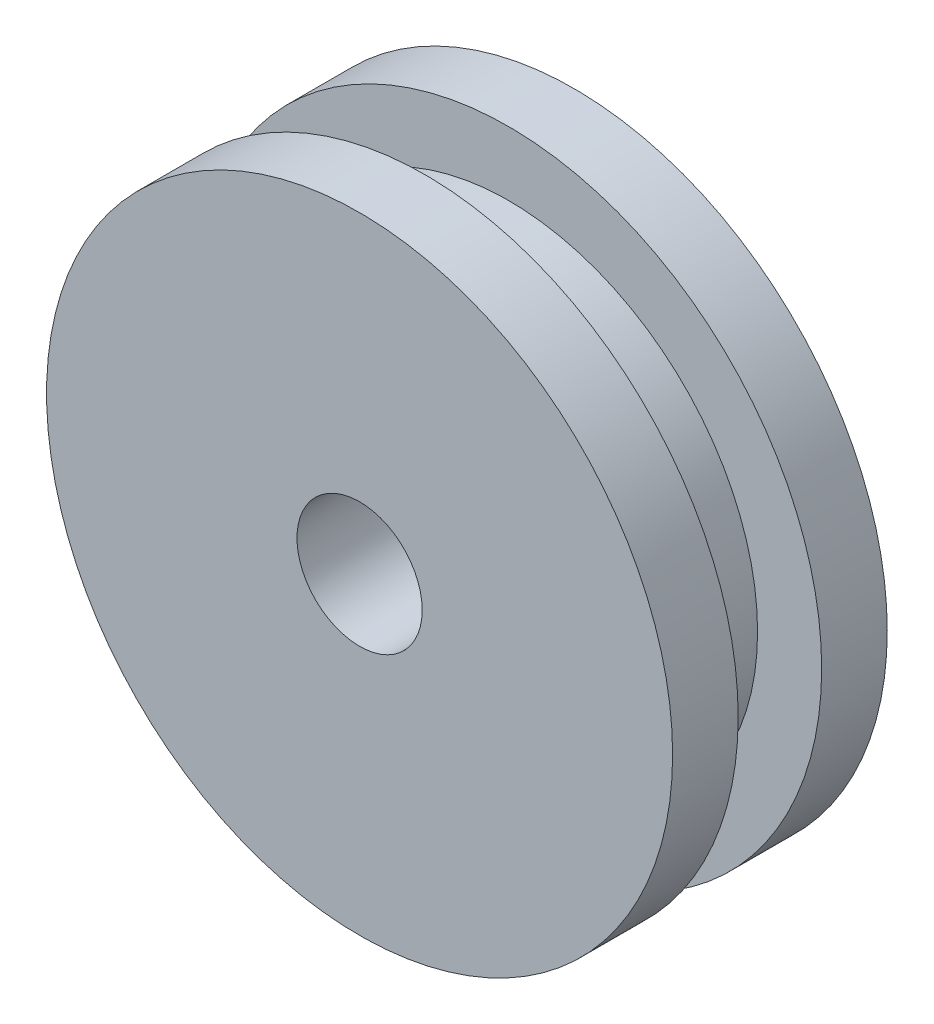
SolidWorks part; units mm, degrees
ref_plane "Front Plane" through (0, 0, 0) normal (0, 0, 1) x (1, 0, 0)
ref_plane "Top Plane" through (0, 0, 0) normal (0, 1, 0) x (1, 0, 0)
ref_plane "Right Plane" through (0, 0, 0) normal (1, 0, 0) x (0, 0, -1)
sketch "S01 - Groove root and axle bore" plane through (0, 0, 0) normal (0, 0, 1) x (1, 0, 0)
  circle A0 centre (0, 0) radius 8.35
  circle A1 centre (0, 0) radius 2.1
  dimension "D1" = 4.2
  dimension "D2" = 16.7
extrude "01 - Groove root and axle bore" add sketch "S01 - Groove root and axle bore" along normal blind 2.8 from offset 1.4
sketch "S02 - Retaining flange -3.6" plane through (0, 0, 0) normal (0, 0, 1) x (1, 0, 0)
  circle A0 centre (0, 0) radius 10.5
  circle A1 centre (0, 0) radius 2.1
  dimension "D1" = 4.2
  dimension "D2" = 21
extrude "02 - Retaining flange -3.6" add sketch "S02 - Retaining flange -3.6" along normal blind 2.2 from offset 3.6
sketch "S03 - Retaining flange 1.4" plane through (0, 0, 0) normal (0, 0, 1) x (1, 0, 0)
  circle A0 centre (0, 0) radius 10.5
  circle A1 centre (0, 0) radius 2.1
  dimension "D1" = 4.2
  dimension "D2" = 21
extrude "03 - Retaining flange 1.4" add sketch "S03 - Retaining flange 1.4" along normal blind 2.2 from offset 1.4
